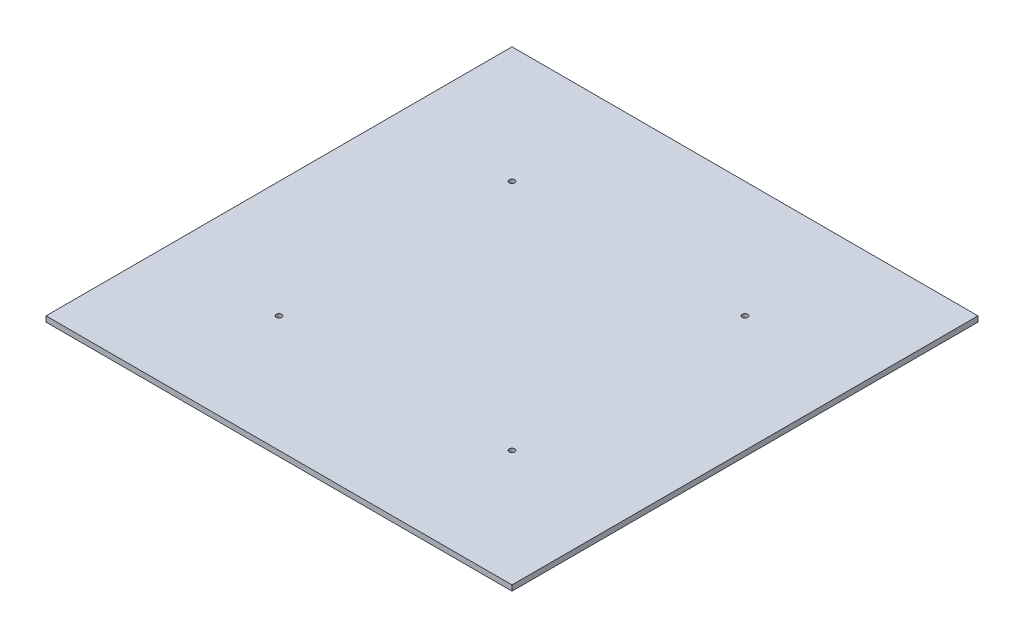
SolidWorks part; units mm, degrees
material "Polyetheretherketone (PEEK)"
ref_plane "Front Plane" through (0, 0, 0) normal (0, 0, 1) x (1, 0, 0)
ref_plane "Top Plane" through (0, 0, 0) normal (0, 1, 0) x (1, 0, 0)
ref_plane "Right Plane" through (0, 0, 0) normal (1, 0, 0) x (0, 0, -1)
sketch "Sketch1" plane through (0, 0, 0) normal (0, 1, 0) x (1, 0, 0)
  line L1 (-128, -128) -> (128, -128)
  line L2 (-128, -128) -> (-128, 128)
  line L3 (-128, 128) -> (128, 128)
  line L4 (128, -128) -> (128, 128)
  line L5 (-128, -128) -> (128, 128) construction
  line L6 (-128, 128) -> (128, -128) construction
  line L7 (-64, -64) -> (64, -64) construction
  line L8 (-64, -64) -> (-64, 64) construction
  line L9 (-64, 64) -> (64, 64) construction
  line L10 (64, -64) -> (64, 64) construction
  line L11 (-64, -64) -> (64, 64) construction
  line L12 (-64, 64) -> (64, -64) construction
  circle A4 centre (-64, 64) radius 1.5
  circle A5 centre (64, 64) radius 1.5
  circle A6 centre (64, -64) radius 1.5
  circle A7 centre (-64, -64) radius 1.5
  point P0 (0, 0)
  point P6 (0, 0)
  dimension "D2" = 3
  dimension "D1" = 256
  dimension "D3" = 128
extrude "Boss-Extrude1" add sketch "Sketch1" along normal mid plane 3
